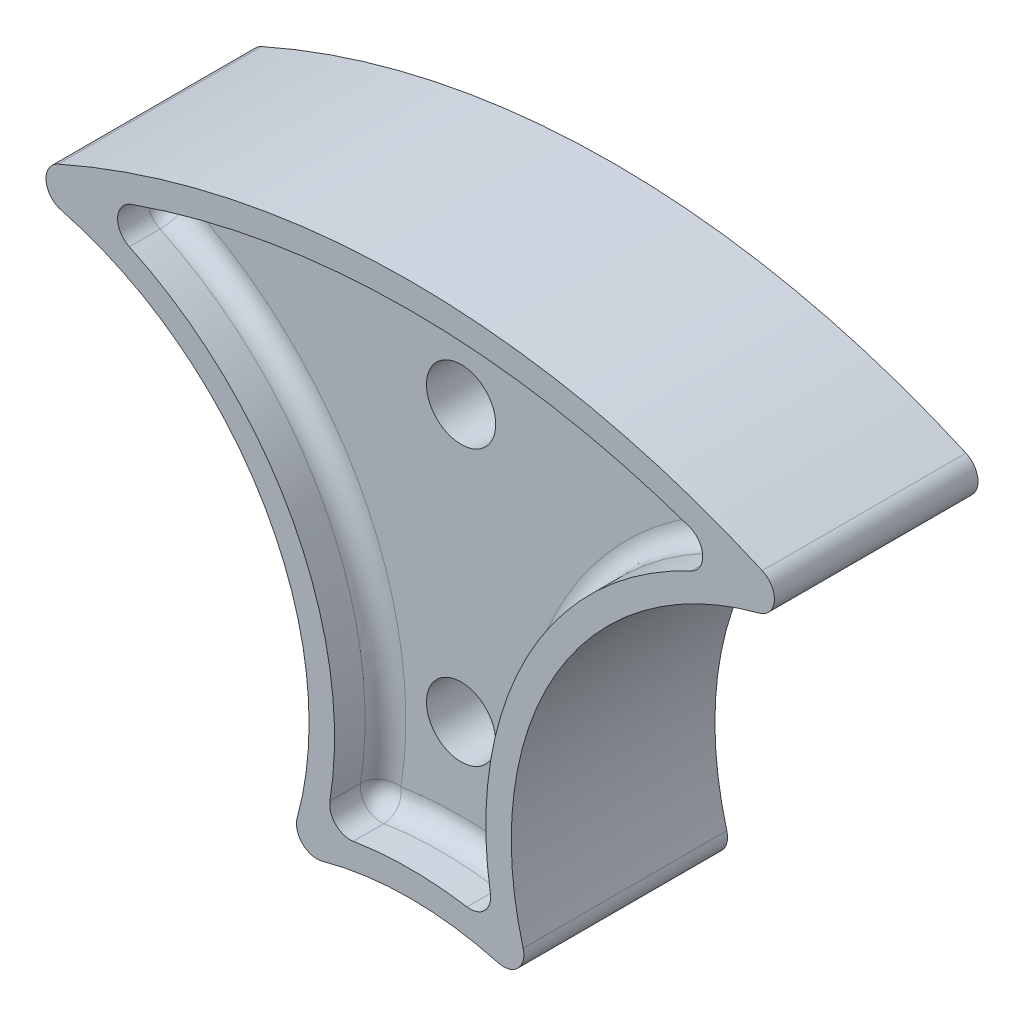
SolidWorks part; units mm, degrees
ref_plane "Front Plane" through (0, 0, 0) normal (0, 0, 1) x (1, 0, 0)
ref_plane "Top Plane" through (0, 0, 0) normal (0, 1, 0) x (1, 0, 0)
ref_plane "Right Plane" through (0, 0, 0) normal (1, 0, 0) x (0, 0, -1)
sketch "Sketch1" plane through (0, 0, 0) normal (0, 0, 1) x (1, 0, 0)
  line L0 (0, 0) -> (0, 60) construction
  line L1 (0, 0) -> (-42.4264, 42.4264) construction
  circle A0 centre (0, 0) radius 32.5 construction
  circle A1 centre (0, 0) radius 60 construction
  circle A2 centre (-42.4264, 42.4264) radius 32.5 construction
  circle A3 centre (42.4264, 42.4264) radius 32.5 construction
  circle A4 centre (0, 0) radius 85 construction
  arc A5 (40.271, 74.8549) -> (-40.271, 74.8549) centre (0, 0) ccw
  arc A6 (-12.3744, 30.052) -> (-40.271, 74.8549) centre (-42.4264, 42.4264) ccw
  arc A7 (12.3744, 30.052) -> (40.271, 74.8549) centre (42.4264, 42.4264) cw
  arc A8 (-12.3744, 30.052) -> (12.3744, 30.052) centre (0, 0) cw
  dimension "D1" = 65
  dimension "D2" = 120
  dimension "D4" = 170
  dimension "D3" = 45
extrude "Boss-Extrude1" add sketch "Sketch1" along normal blind 20
fillet "Fillet1" radius 2 4 edges at (12.3744, 30.052, 10) (-12.3744, 30.052, 10) (-40.271, 74.8549, 10) (40.271, 74.8549, 10)
sketch "Sketch6" plane through (0, 0, 20) normal (0, 0, 1) x (1, 0, 0)
  arc A8 (32.279, 75.9231) -> (-32.279, 75.9231) centre (0, 0) ccw
  arc A9 (-8.4657, 33.9608) -> (-32.279, 75.9231) centre (-42.4264, 42.4264) ccw
  arc A10 (8.4657, 33.9608) -> (-8.4657, 33.9608) centre (0, 0) ccw
  arc A11 (32.279, 75.9231) -> (8.4657, 33.9608) centre (42.4264, 42.4264) ccw
  arc A12 (32.279, 75.9231) -> (-32.279, 75.9231) centre (0, 0) ccw
  arc A13 (-8.4657, 33.9608) -> (-32.279, 75.9231) centre (-42.4264, 42.4264) ccw
  arc A14 (8.4657, 33.9608) -> (-8.4657, 33.9608) centre (0, 0) ccw
  arc A15 (32.279, 75.9231) -> (8.4657, 33.9608) centre (42.4264, 42.4264) ccw
  dimension "D1" = 2.5
extrude "Recess" cut sketch "Sketch6" against normal blind 5
fillet "Recess Fillet" radius 2 8 edges at (0, 82.5, 15) (-11.9864, 59.7009, 15) (0, 35, 15) (11.9864, 59.7009, 15) (8.4657, 33.9608, 17.5) (-8.4657, 33.9608, 17.5) (32.279, 75.9231, 17.5) (-32.279, 75.9231, 17.5)
sketch "Sketch2" plane through (0, 0, 20) normal (0, 0, 1) x (1, 0, 0)
  line L0 (0, 0) -> (0, 32.5) construction
  line L1 (0, 32.5) -> (0, 85) construction
  arc A2 (12.3744, 30.052) -> (-12.3744, 30.052) centre (0, 0) ccw construction
  arc A3 (40.271, 74.8549) -> (-40.271, 74.8549) centre (0, 0) ccw construction
  point P6 (0, 45)
  point P12 (0, 72)
  dimension "D1" = 12.5
  dimension "D2" = 72
  dimension "D3" = 45
  dimension "D4" = 27
  dimension "D5" = 13
hole_wizard "M8x1.25 Tapped Hole2" positions "Sketch4" profile "Sketch5" tap size "M8x1.25" standard "ANSI Metric" end condition through all
sketch "Sketch4" plane through (0, 0, 20) normal (0, 0, 1) x (1, 0, 0)
  point P0 (0, 45)
  point P3 (0, 72)
sketch "Sketch5" plane through (0, 45, 20) normal (1, 0, 0) x (0, -1, 0)
  line L0 (0, 0) -> (0, 20)
  line L1 (0, 20) -> (4.5, 20)
  line L2 (3.4, 18.9) -> (3.4, 1.1)
  line L3 (3.4, 1.1) -> (4.5, 0)
  line L5 (4.5, 0) -> (0, 0)
  line L6 (-3.4, 1.1) -> (-4.5, 0) construction
  line L7 (4.5, 20) -> (3.4, 18.9)
  line L8 (-4.5, 20) -> (-3.4, 18.9) construction
  line L11 (0, -6.35) -> (0, 107.95) construction
  dimension "Thru Tap Drill Dia." = 6.8
  dimension "Thru Tap Drill Depth" = 20
  dimension "Near C'Sink Dia." = 9
  dimension "Near C'Sink Angle" = 90
  dimension "Far C'Sink Dia." = 9
  dimension "Far C'Sink Angle" = 90
cosmetic thread "Hole Thread3" parameters "D2"=8
cosmetic thread "Hole Thread4" parameters "D2"=8
equation "\"a\"= 1"
equation "\"b\"= 1"
equation "\"c\"= 1"
equation "\"d\"= 1"
equation "\"e\"= 1"
equation "\"x\"= 1"
equation "\"y\"= 1"
equation "\"z\"= 1"
